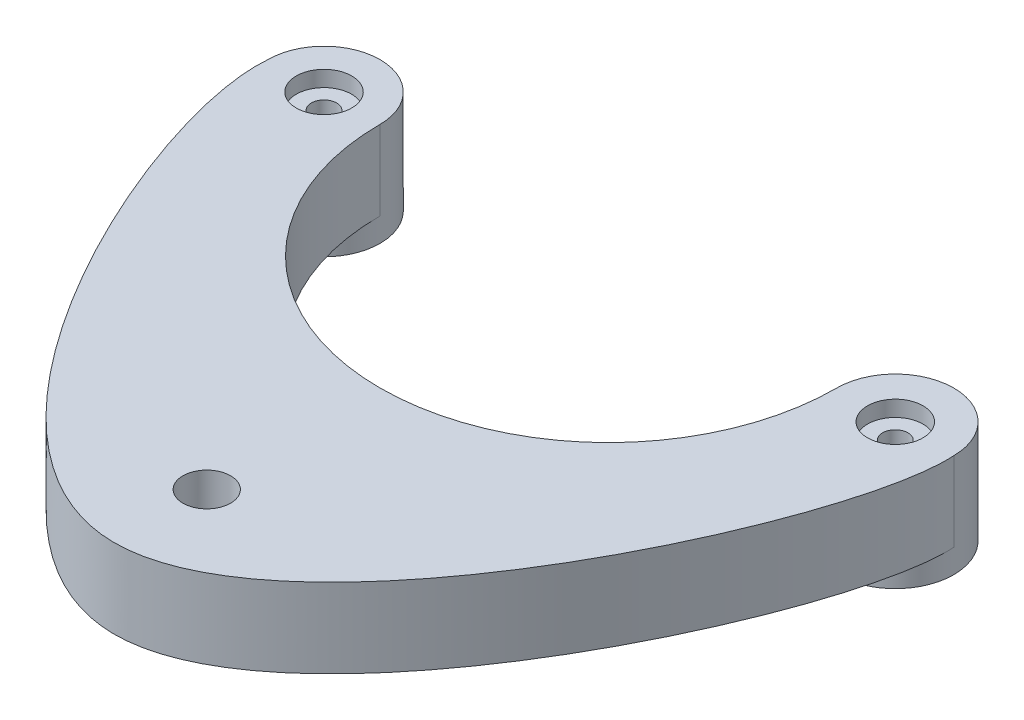
SolidWorks part; units mm, degrees
ref_plane "Front Plane" through (0, 0, 0) normal (0, 0, 1) x (1, 0, 0)
ref_plane "Top Plane" through (0, 0, 0) normal (0, 1, 0) x (1, 0, 0)
ref_plane "Right Plane" through (0, 0, 0) normal (1, 0, 0) x (0, 0, -1)
sketch "Sketch6" plane through (0, 0, 0) normal (0, 1, 0) x (1, 0, 0)
  circle A0 centre (-18, 0) radius 3.5334
  circle A1 centre (18, 0) radius 3.6885
  dimension "D1" = 18
  dimension "D2" = 18
extrude "Boss-Extrude4" add sketch "Sketch6" against normal blind 1.5
sketch "Sketch7" plane through (0, 0, 0) normal (0, 1, 0) x (1, 0, 0)
  arc A2 (14.3115, 0) -> (-14.4666, 0) centre (-0.0775, 0) cw
  circle A3 centre (18, 0) radius 3.6885 construction
  circle A4 centre (-18, 0) radius 3.5334 construction
  arc A8 (14.3115, 0) -> (21.6885, 0) centre (18, 0) cw
  arc A9 (-14.4666, 0) -> (-21.5334, 0) centre (-18, 0) ccw
  spline S0 degree 3 poles (-21.5334, 0) (-22.1952, -7.2155) (0.0377, -55.23) (22.1808, -7.1441) (21.6885, 0) knots 0 0 0 0 0.499656 1 1 1 1
extrude "Boss-Extrude5" add sketch "Sketch7" along normal blind 5
sketch "Sketch10" plane through (0, 5, 0) normal (0, 1, 0) x (1, 0, 0)
  circle A0 centre (0, -24.1497) radius 4
  dimension "D1" = 8
extrude "Boss-Extrude7" [suppressed] add sketch "Sketch10" along normal blind 70
fillet "Fillet3" [suppressed] radius 3
sketch "Sketch11" plane through (0, -1.5, 0) normal (0, -1, 0) x (-1, 0, 0)
  circle A0 centre (-18, 0) radius 1.2
  circle A1 centre (18, 0) radius 1.2
  dimension "D1" = 2.4
  dimension "D2" = 2.4
extrude "Boss-Extrude8" [suppressed] add sketch "Sketch11" along normal blind 2
sketch "Sketch12" plane through (0, 5, 0) normal (0, 1, 0) x (1, 0, 0)
  circle A0 centre (-18, 0) radius 0.8
  circle A1 centre (18, 0) radius 0.8
  dimension "D1" = 1.6
  dimension "D2" = 1.6
extrude "Cut-Extrude3" cut sketch "Sketch12" against normal through all
sketch "Sketch13" plane through (0, 5, 0) normal (0, 1, 0) x (1, 0, 0)
  circle A0 centre (-18, 0) radius 1.75
  circle A1 centre (18, 0) radius 1.75
  dimension "D1" = 3.5
  dimension "D2" = 3.5
extrude "Screw Inset Cut" cut sketch "Sketch13" against normal blind 1
sketch "Sketch14" plane through (0, 5, 0) normal (0, 1, 0) x (1, 0, 0)
  line L1 (-15.5757, 6.529) -> (15.5757, 6.529)
  line L2 (-15.5757, 6.529) -> (-15.5757, -6.529)
  line L3 (-15.5757, -6.529) -> (15.5757, -6.529)
  line L4 (15.5757, 6.529) -> (15.5757, -6.529)
  line L5 (-15.5757, 6.529) -> (15.5757, -6.529) construction
  line L6 (-15.5757, -6.529) -> (15.5757, 6.529) construction
  point P0 (0, 0)
extrude "Headstage Cutout" [suppressed] cut sketch "Sketch14" against normal through all
fillet "Fillet7" [suppressed] radius 1
fillet "Fillet8" [suppressed] radius 1
fillet "Fillet9" [suppressed] radius 1
sketch "Sketch15" plane through (0, 5, 0) normal (0, 1, 0) x (1, 0, 0)
  circle A0 centre (0, -25.3866) radius 1.5
extrude "Cut-Extrude4" cut sketch "Sketch15" against normal up to next
